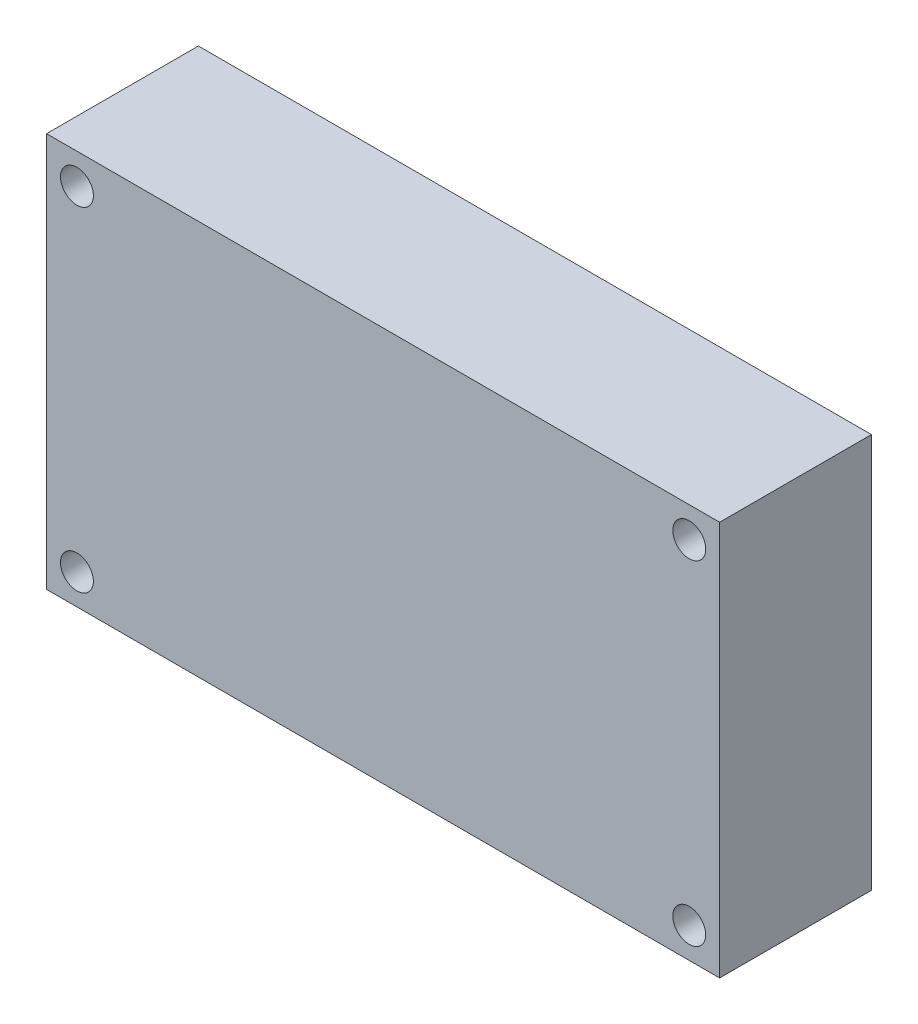
SolidWorks part; units mm, degrees
ref_plane "前视基准面" through (0, 0, 0) normal (0, 0, 1) x (1, 0, 0)
ref_plane "上视基准面" through (0, 0, 0) normal (0, 1, 0) x (1, 0, 0)
ref_plane "右视基准面" through (0, 0, 0) normal (1, 0, 0) x (0, 0, -1)
sketch "草图1" plane through (0, 0, 0) normal (0, 0, 1) x (1, 0, 0)
  line L0 (-30.25, -16.5) -> (30.25, -16.5) construction
  line L1 (-33.25, -19.5) -> (33.25, -19.5)
  line L2 (-33.25, -19.5) -> (-33.25, 19.5)
  line L3 (-33.25, 19.5) -> (33.25, 19.5)
  line L4 (33.25, -19.5) -> (33.25, 19.5)
  line L5 (0, 19.5) -> (0, -19.5) construction
  line L6 (-33.25, 0) -> (33.25, 0) construction
  line L7 (-30.25, 16.5) -> (30.25, 16.5) construction
  line L8 (-30.25, 16.5) -> (-30.25, -16.5) construction
  line L9 (30.25, 16.5) -> (30.25, -16.5) construction
  line L10 (-30.25, 19.5) -> (-30.25, -19.5) construction
  line L11 (-33.25, 16.5) -> (33.25, 16.5) construction
  line L12 (-33.25, -16.5) -> (33.25, -16.5) construction
  line L13 (30.25, 19.5) -> (30.25, -19.5) construction
  circle A0 centre (-30.25, 16.5) radius 1.625
  circle A1 centre (30.25, 16.5) radius 1.625
  circle A2 centre (30.25, -16.5) radius 1.625
  circle A3 centre (-30.25, -16.5) radius 1.625
  point P0 (0, 0)
  dimension "D1" = 66.5
  dimension "D2" = 39
  dimension "D3" = 16.5
  dimension "D4" = 16.5
  dimension "D5" = 30.25
  dimension "D6" = 30.25
extrude "凸台-拉伸1" add sketch "草图1" along normal blind 15
